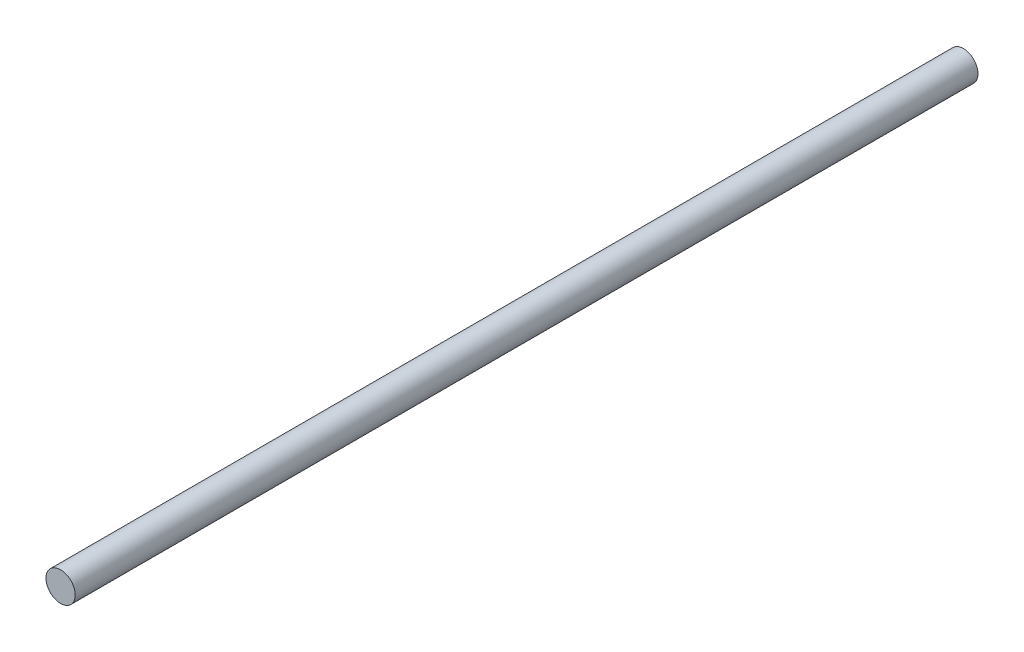
SolidWorks part; units mm, degrees
material "Plain Carbon Steel"
ref_plane "Front Plane" through (0, 0, 0) normal (0, 0, 1) x (1, 0, 0)
ref_plane "Top Plane" through (0, 0, 0) normal (0, 1, 0) x (1, 0, 0)
ref_plane "Right Plane" through (0, 0, 0) normal (1, 0, 0) x (0, 0, -1)
sketch "Sketch1" plane through (0, 0, 0) normal (0, 0, 1) x (1, 0, 0)
  circle A0 centre (0, 0) radius 3.175
  dimension "D1" = 6.35
extrude "Boss-Extrude1" add sketch "Sketch1" along normal blind 196
